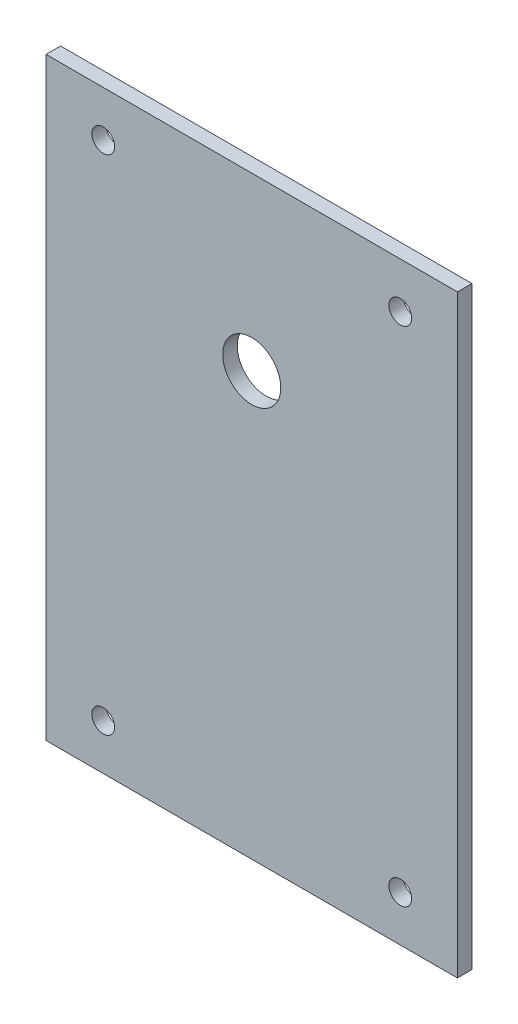
SolidWorks part; units mm, degrees
material "Custom Plastic"
ref_plane "Front Plane" through (0, 0, 0) normal (0, 0, 1) x (1, 0, 0)
ref_plane "Top Plane" through (0, 0, 0) normal (0, 1, 0) x (1, 0, 0)
ref_plane "Right Plane" through (0, 0, 0) normal (1, 0, 0) x (0, 0, -1)
sketch "Sketch1" plane through (0, 0, 0) normal (0, 0, 1) x (1, 0, 0)
  line L1 (-90, 130) -> (0, 130)
  line L2 (-90, 130) -> (-90, 0)
  line L3 (-90, 0) -> (0, 0)
  line L4 (0, 130) -> (0, 0)
  dimension "D1" = 130
  dimension "D2" = 90
extrude "Boss-Extrude1" add sketch "Sketch1" along normal blind 3.175
sketch "Sketch2" plane through (0, 0, 3.175) normal (0, 0, 1) x (1, 0, 0)
  line L2 (0, 130) -> (-90, 130) construction
  circle A0 centre (-77.5, 120) radius 2.5
  circle A1 centre (-12.5, 120) radius 2.5
  point P4 (-45, 130)
  dimension "D1" = 5
  dimension "D2" = 5
  dimension "D3" = 32.5
  dimension "D4" = 32.5
  dimension "D5" = 10
  dimension "D6" = 10
extrude "Cut-Extrude1" cut sketch "Sketch2" against normal up to surface (3.175 mm away) up to face at (-45, 65, 0)
ref_plane "Plane1" through (0, 65, 0) normal (0, 1, 0) x (1, 0, 0)
mirror "Mirror1" about plane through (0, 65, 0) normal (0, 1, 0) of "Cut-Extrude1"
sketch "Sketch3" plane through (0, 0, 3.175) normal (0, 0, 1) x (1, 0, 0)
  line L2 (-45, 130) -> (-45, 0) construction
  line L3 (0, 130) -> (-90, 130) construction
  line L4 (-90, 0) -> (0, 0) construction
  line L5 (-90, 65) -> (0, 65) construction
  line L6 (-90, 130) -> (-90, 0) construction
  line L7 (0, 0) -> (0, 130) construction
  circle A1 centre (-45, 92.5) radius 6.35
  dimension "D1" = 37.5
  dimension "D2" = 12.7
extrude "Cut-Extrude2" cut sketch "Sketch3" against normal up to surface (3.175 mm away) up to face at (-75, 10, 0)
